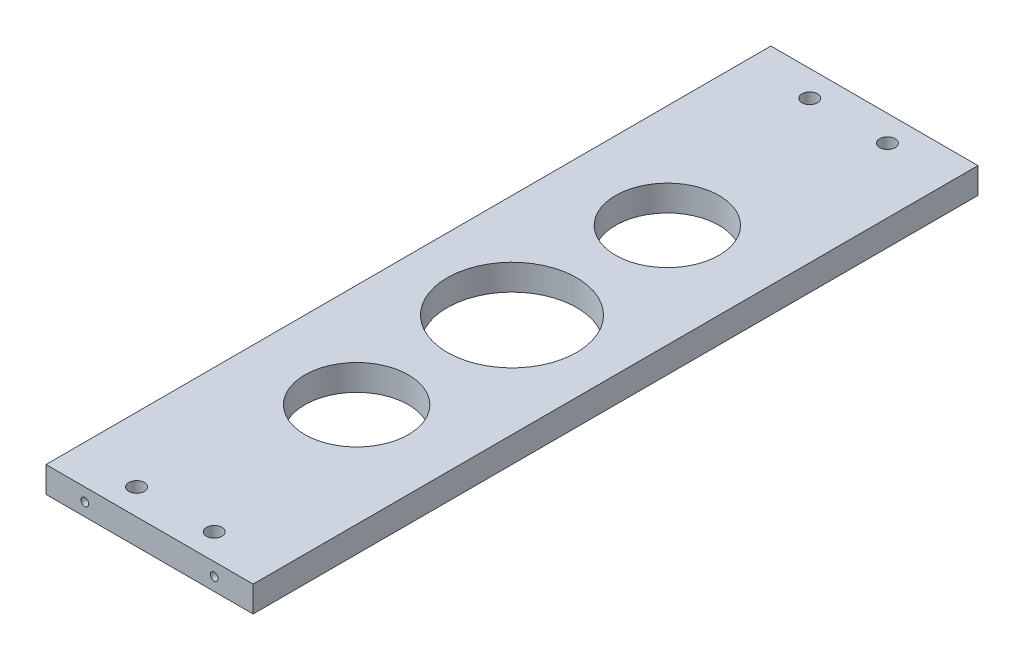
SolidWorks part; units mm, degrees
material "ABS PC"
ref_plane "Спереди" through (0, 0, 0) normal (0, 0, 1) x (1, 0, 0)
ref_plane "Сверху" through (0, 0, 0) normal (0, 1, 0) x (1, 0, 0)
ref_plane "Справа" through (0, 0, 0) normal (1, 0, 0) x (0, 0, -1)
sketch "Sketch1" plane through (0, 0, 0) normal (0, 1, 0) x (1, 0, 0)
  line L0 (0, -110) -> (0, 110)
  line L1 (0, 140) -> (80, 140)
  line L2 (0, 140) -> (0, 110)
  line L3 (0, -140) -> (80, -140)
  line L4 (80, 140) -> (80, 110)
  line L5 (80, 110) -> (80, -110)
  line L10 (0, -110) -> (0, -140)
  line L11 (80, -110) -> (80, -140)
  circle A0 centre (25, 130) radius 3
  circle A1 centre (55, 130) radius 3
  circle A2 centre (25, -130) radius 3
  circle A3 centre (55, -130) radius 3
  circle A4 centre (40, 0) radius 25
  circle A5 centre (40, -60) radius 20
  circle A6 centre (40, 60) radius 20
  dimension "D1" = 10
  dimension "D3" = 10
  dimension "D4" = 25
  dimension "D6" = 6
  dimension "D7" = 30
  dimension "D8" = 40
  dimension "D9" = 30
  dimension "D11" = 50
  dimension "D12" = 40
  dimension "D13" = 60
  dimension "D14" = 60
  dimension "D15" = 40
  dimension "D2" = 280
  dimension "D5" = 80
  dimension "D10" = 30
extrude "Boss-Extrude1" add sketch "Sketch1" along normal blind 10
sketch "Sketch2" plane through (0, 0, 140) normal (0, 0, 1) x (1, 0, 0)
  line L0 (0, 0) -> (80, 0) construction
  line L2 (0, 10) -> (0, 0) construction
  line L3 (80, 10) -> (80, 0) construction
  circle A0 centre (15, 5) radius 1.5
  circle A1 centre (65, 5) radius 1.5
  dimension "D1" = 5
  dimension "D2" = 3
  dimension "D3" = 15
  dimension "D4" = 15
extrude "Cut-Extrude1" cut sketch "Sketch2" against normal blind 15
mirror "Mirror1" about plane through (0, 0, 0) normal (0, 0, 1) of "Cut-Extrude1"
